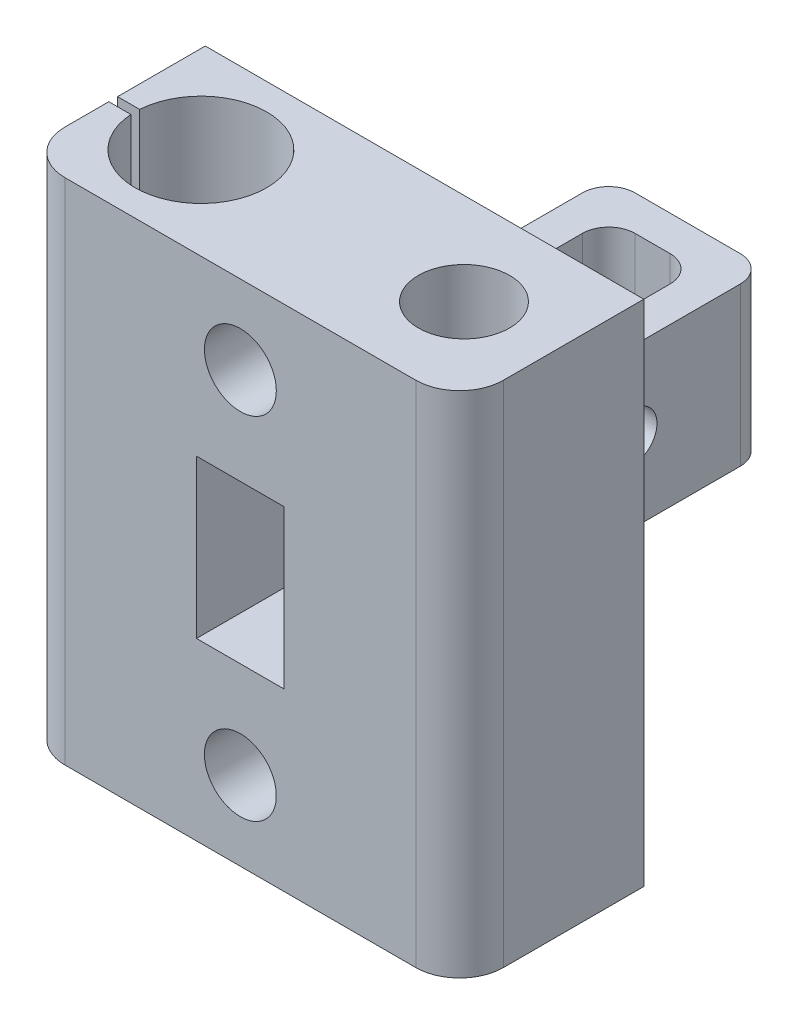
SolidWorks part; units mm, degrees
ref_plane "Front Plane" through (0, 0, 0) normal (0, 0, 1) x (1, 0, 0)
ref_plane "Top Plane" through (0, 0, 0) normal (0, 1, 0) x (1, 0, 0)
ref_plane "Right Plane" through (0, 0, 0) normal (1, 0, 0) x (0, 0, -1)
sketch "Sketch1" plane through (0, 0, 0) normal (0, 1, 0) x (1, 0, 0)
  line L1 (-25, 10.5) -> (25, 10.5)
  line L2 (-25, 10.5) -> (-25, -10.5)
  line L3 (-25, -10.5) -> (25, -10.5)
  line L4 (25, 10.5) -> (25, -10.5)
  line L5 (-25, 10.5) -> (25, -10.5) construction
  line L6 (-25, -10.5) -> (25, 10.5) construction
  point P0 (0, 0)
  dimension "D1" = 21
  dimension "D2" = 50
extrude "Boss-Extrude1" add sketch "Sketch1" along normal blind 58
sketch "Sketch3" plane through (0, 58, 0) normal (0, 1, 0) x (1, 0, 0)
  line L0 (-15, 0) -> (15, 0) construction
  circle A0 centre (-15, 0) radius 7.5
  dimension "D1" = 15
  dimension "D2" = 30
extrude "Cut-Extrude1" cut sketch "Sketch3" against normal blind 24 contours A0
sketch "Sketch4" plane through (0, 58, 0) normal (0, 1, 0) x (1, 0, 0)
  line L0 (-15, 0) -> (15, 0) construction
  circle A0 centre (15, 0) radius 5.2
  dimension "D1" = 10.4
extrude "Cut-Extrude2" cut sketch "Sketch4" against normal up to next
sketch "Sketch5" plane through (0, 0, 0) normal (0, -1, 0) x (1, 0, 0)
  circle A1 centre (-15, 0) radius 7.5
  circle A2 centre (-15, 0) radius 7.5
  dimension "D1" = 0
extrude "Cut-Extrude3" cut sketch "Sketch5" against normal blind 24
sketch "Sketch6" plane through (0, 0, 0) normal (0, -1, 0) x (1, 0, 0)
  circle A0 centre (-15, 0) radius 4.5
extrude "Cut-Extrude4" cut sketch "Sketch6" against normal up to next
sketch "Sketch7" plane through (0, 0, 10.5) normal (0, 0, 1) x (1, 0, 0)
  line L0 (0, 58) -> (0, 0) construction
  line L1 (-25, 58) -> (25, 58) construction
  line L2 (-25, 0) -> (25, 0) construction
  line L3 (-25, 29) -> (25, 29) construction
  line L4 (-25, 58) -> (-25, 0) construction
  line L5 (25, 58) -> (25, 0) construction
  circle A1 centre (0, 49) radius 4.1
  circle A2 centre (0, 9) radius 4.1
  point P24 (0, 9)
  dimension "D1" = 8.2
  dimension "D2" = 9
sketch "Sketch8" plane through (0, 0, 10.5) normal (0, 0, 1) x (1, 0, 0)
  line L0 (-25, 29) -> (25, 29) construction
  line L1 (-25, 58) -> (-25, 0) construction
  line L2 (25, 58) -> (25, 0) construction
  line L3 (0, 58) -> (0, 0) construction
  line L4 (-25, 58) -> (25, 58) construction
  line L6 (-5, 20) -> (5, 20)
  line L7 (-5, 20) -> (-5, 38)
  line L8 (-5, 38) -> (5, 38)
  line L9 (5, 20) -> (5, 38)
  line L10 (-5, 20) -> (5, 38) construction
  line L11 (-5, 38) -> (5, 20) construction
  point P11 (0, 29)
  dimension "D1" = 18
  dimension "D2" = 10
extrude "Cut-Extrude5" cut sketch "Sketch8" against normal up to next
sketch "Sketch10" plane through (0, 0, -10.5) normal (0, 0, -1) x (-1, 0, 0)
  line L0 (-25, 29) -> (25, 29) construction
  line L1 (-25, 58) -> (-25, 0) construction
  line L2 (25, 58) -> (25, 0) construction
  line L3 (0, 58) -> (0, 0) construction
  line L4 (-25, 58) -> (25, 58) construction
extrude "Cut-Extrude6" cut sketch "Sketch7" against normal blind 15
sketch "Sketch11" plane through (0, 0, -10.5) normal (0, 0, -1) x (-1, 0, 0)
  line L0 (-25, 29) -> (25, 29) construction
  line L1 (9, 38) -> (5, 38)
  line L2 (9, 38) -> (9, 20)
  line L3 (9, 20) -> (5, 20)
  line L4 (5, 38) -> (5, 20)
  line L5 (9, 38) -> (5, 20) construction
  line L6 (9, 20) -> (5, 38) construction
  line L7 (0, 58) -> (0, 0) construction
  line L8 (0, 58) -> (0, 0)
  line L9 (-9, 20) -> (-5, 20)
  line L10 (-5, 38) -> (-5, 20)
  line L11 (-9, 38) -> (-5, 38)
  line L12 (-9, 38) -> (-9, 20)
  point P0 (7, 29)
  line M7 (-5, 20) -> (-5, 38)
  line M9 (5, 38) -> (5, 20)
  dimension "D1" = 5
  dimension "D2" = 4
  dimension "D3" = 18
extrude "Boss-Extrude2" add sketch "Sketch11" along normal blind 26 contours L1 L4 L3 L2 M9 | L11 L12 L9 L10 M7
sketch "Sketch12" plane through (0, 0, -36.5) normal (0, 0, -1) x (-1, 0, 0)
  line L1 (9, 20) -> (-9, 20)
  line L2 (9, 20) -> (9, 38)
  line L3 (9, 38) -> (-9, 38)
  line L4 (-9, 20) -> (-9, 38)
extrude "Boss-Extrude3" add sketch "Sketch12" along normal blind 4
sketch "Sketch13" plane through (9, 0, 0) normal (1, 0, 0) x (0, 0, -1)
  line L3 (10.5, 29) -> (40.5, 29) construction
  line L4 (10.5, 38) -> (10.5, 20) construction
  line L5 (40.5, 38) -> (40.5, 20) construction
  line L6 (16.25, 29) -> (25.25, 29) construction
  line L7 (16.25, 31.75) -> (25.25, 31.75)
  line L8 (16.25, 26.25) -> (25.25, 26.25)
  arc A0 (16.25, 31.75) -> (16.25, 26.25) centre (16.25, 29) ccw
  arc A1 (25.25, 26.25) -> (25.25, 31.75) centre (25.25, 29) ccw
  point P1 (13.5, 29)
  point P14 (20.75, 29)
  dimension "D1" = 5.5
  dimension "D2" = 3
  dimension "D3" = 9
extrude "Cut-Extrude7" cut sketch "Sketch13" against normal through all
fillet "Fillet1" radius 5 2 edges at (-25, 29, 10.5) (25, 29, 10.5)
fillet "Fillet2" radius 5 4 edges at (-7, 20, -10.5) (7, 20, -10.5) (-7, 38, -10.5) (7, 38, -10.5)
fillet "Fillet3" radius 3 4 edges at (-5, 29, -36.5) (5, 29, -36.5) (-9, 29, -40.5) (9, 29, -40.5)
sketch "Sketch14" plane through (0, 0, 0) normal (0, -1, 0) x (1, 0, 0)
  line L0 (20.5508, 5.5508) -> (9.4492, -5.5508) construction
  line L1 (25, -10.5) -> (-25, -10.5) construction
  circle A0 centre (20.5508, 5.5508) radius 1.95
  circle A1 centre (15, 0) radius 5.2 construction
  circle A2 centre (9.4492, -5.5508) radius 1.95
  circle A3 centre (15, 0) radius 5.2 construction
  dimension "D1" = 7.85
  dimension "D2" = 3.9
  dimension "D3" = 3.9
  dimension "D4" = 7.85
  dimension "D5" = 45
extrude "Cut-Extrude8" cut sketch "Sketch14" against normal blind 10
sketch "Sketch15" plane through (0, 58, 0) normal (0, 1, 0) x (1, 0, 0)
  line L0 (-25, 10.5) -> (-25, -5.5) construction
  line L1 (-25, -0.5) -> (-19.4721, -0.5)
  line L2 (-25, -0.5) -> (-25, 0.5)
  line L3 (-25, 0.5) -> (-19.4721, 0.5)
  line L4 (-19.4721, -0.5) -> (-19.4721, 0.5)
  circle A2 centre (-15, 0) radius 4.5 construction
  dimension "D1" = 1
extrude "Cut-Extrude9" cut sketch "Sketch15" against normal through all
